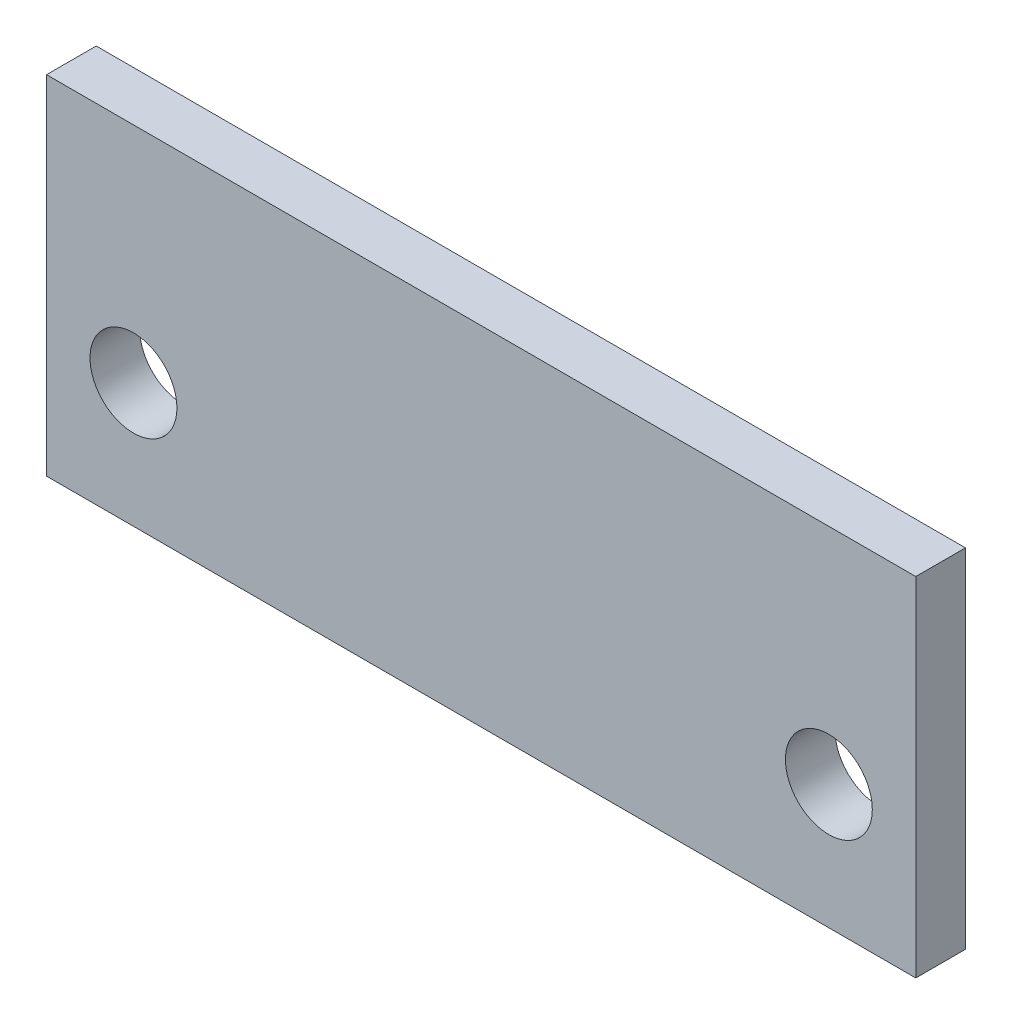
SolidWorks part; units mm, degrees
material "ABS"
ref_plane "Front Plane" through (0, 0, 0) normal (0, 0, 1) x (1, 0, 0)
ref_plane "Top Plane" through (0, 0, 0) normal (0, 1, 0) x (1, 0, 0)
ref_plane "Right Plane" through (0, 0, 0) normal (1, 0, 0) x (0, 0, -1)
sketch "Sketch1" plane through (0, 0, 0) normal (0, 1, 0) x (1, 0, 0)
  line L1 (-17.5, -1) -> (17.5, -1)
  line L2 (-17.5, -1) -> (-17.5, 1)
  line L3 (-17.5, 1) -> (17.5, 1)
  line L4 (17.5, -1) -> (17.5, 1)
  line L5 (-17.5, -1) -> (17.5, 1) construction
  line L6 (-17.5, 1) -> (17.5, -1) construction
  point P0 (0, 0)
  dimension "D1" = 2
  dimension "D2" = 35
extrude "Boss-Extrude1" add sketch "Sketch1" along normal blind 14
sketch "Sketch2" plane through (0, 0, 1) normal (0, 0, 1) x (1, 0, 0)
  line L0 (-17.5, 14) -> (-17.5, 0) construction
  line L1 (-17.5, 0) -> (17.5, 0) construction
  line L2 (17.5, 14) -> (17.5, 0) construction
  circle A0 centre (-14, 5) radius 1.75
  circle A1 centre (14, 5) radius 1.75
  dimension "D1" = 3.5
  dimension "D3" = 5
  dimension "D4" = 3.5
  dimension "D2" = 3.5
  dimension "D5" = 3.5
extrude "Cut-Extrude1" cut sketch "Sketch2" against normal blind 14
